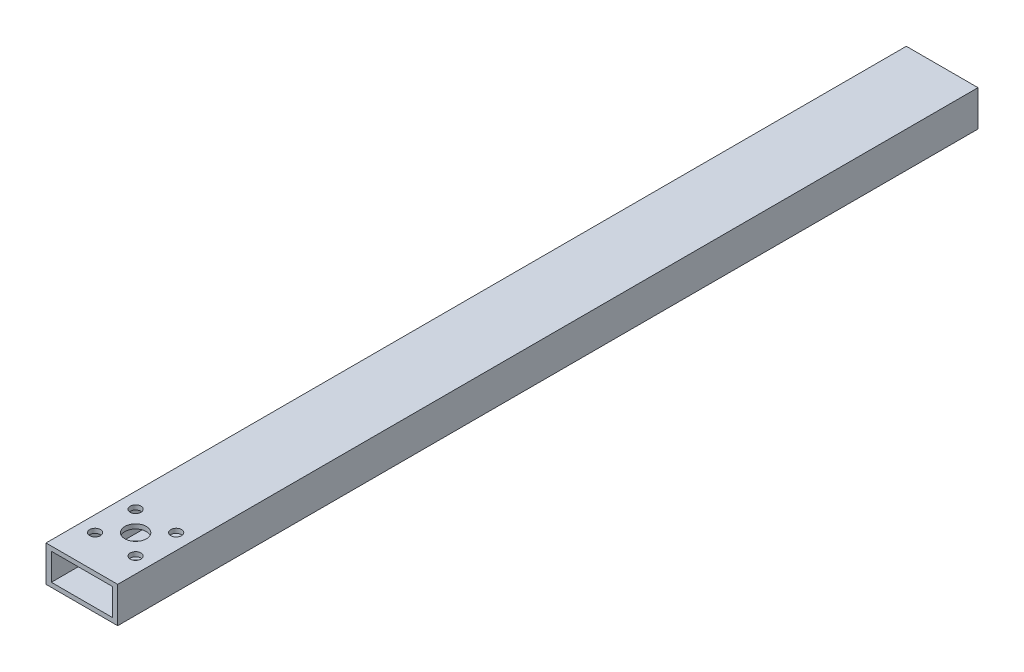
SolidWorks part; units mm, degrees
ref_plane "前视基准面" through (0, 0, 0) normal (0, 0, 1) x (1, 0, 0)
ref_plane "上视基准面" through (0, 0, 0) normal (0, 1, 0) x (1, 0, 0)
ref_plane "右视基准面" through (0, 0, 0) normal (1, 0, 0) x (0, 0, -1)
sketch "草图1" plane through (0, 0, 0) normal (0, 0, 1) x (1, 0, 0)
  line L1 (-10, 5) -> (10, 5)
  line L2 (-10, 5) -> (-10, -5)
  line L3 (-10, -5) -> (10, -5)
  line L4 (10, 5) -> (10, -5)
  line L5 (-10, 5) -> (10, -5) construction
  line L6 (-10, -5) -> (10, 5) construction
  line L7 (-8.5, 3.75) -> (8.5, 3.75)
  line L8 (-8.5, 3.75) -> (-8.5, -3.75)
  line L9 (-8.5, -3.75) -> (8.5, -3.75)
  line L10 (8.5, 3.75) -> (8.5, -3.75)
  line L11 (-8.5, 3.75) -> (8.5, -3.75) construction
  line L12 (-8.5, -3.75) -> (8.5, 3.75) construction
  point P0 (0, 0)
  point P5 (0, 0)
  dimension "D1" = 20
  dimension "D2" = 10
  dimension "D3" = 17
  dimension "D4" = 7.5
extrude "凸台-拉伸1" add sketch "草图1" along normal blind 200
sketch "草图3" plane through (0, -5, 0) normal (0, -1, 0) x (1, 0, 0)
  line L0 (0, -5.5) -> (0, 5.5) construction
  line L1 (-10, 200) -> (10, 200) construction
  circle A0 centre (0, 185) radius 3
  point P4 (0, 0)
  point P7 (0, 0)
  dimension "D1" = 6
  dimension "D2" = 15
extrude "切除-拉伸2" cut sketch "草图3" against normal blind 10
sketch "草图5" plane through (0, -5, 0) normal (0, -1, 0) x (1, 0, 0)
  line L0 (0, 185) -> (17.4403, 202.4403) construction
  line L1 (0, 185) -> (20.2053, 185) construction
  circle A0 centre (0, 185) radius 8 construction
  circle A1 centre (5.6569, 190.6569) radius 1.5
  circle A2 centre (5.6569, 179.3431) radius 1.5
  circle A3 centre (-5.6569, 179.3431) radius 1.5
  circle A4 centre (-5.6569, 190.6569) radius 1.5
  point P16 (0, 185)
  dimension "D1" = 45
  dimension "D2" = 4
extrude "切除-拉伸4" cut sketch "草图5" against normal blind 10
sketch "草图6" plane through (0, 0, 0) normal (0, 0, -1) x (-1, 0, 0)
  line L1 (-8.5, -3.75) -> (8.5, -3.75)
  line L2 (-8.5, -3.75) -> (-8.5, 3.75)
  line L3 (-8.5, 3.75) -> (8.5, 3.75)
  line L4 (8.5, -3.75) -> (8.5, 3.75)
  line L5 (-8.5, -3.75) -> (8.5, 3.75) construction
  line L6 (-8.5, 3.75) -> (8.5, -3.75) construction
  line L7 (-10, -5) -> (10, -5)
  line L8 (-10, -5) -> (-10, 5)
  line L9 (-10, 5) -> (10, 5)
  line L10 (10, -5) -> (10, 5)
  line L11 (-10, -5) -> (10, 5) construction
  line L12 (-10, 5) -> (10, -5) construction
  point P0 (0, 0)
  point P5 (0, 0)
extrude "凸台-拉伸2" add sketch "草图6" along normal blind 40
